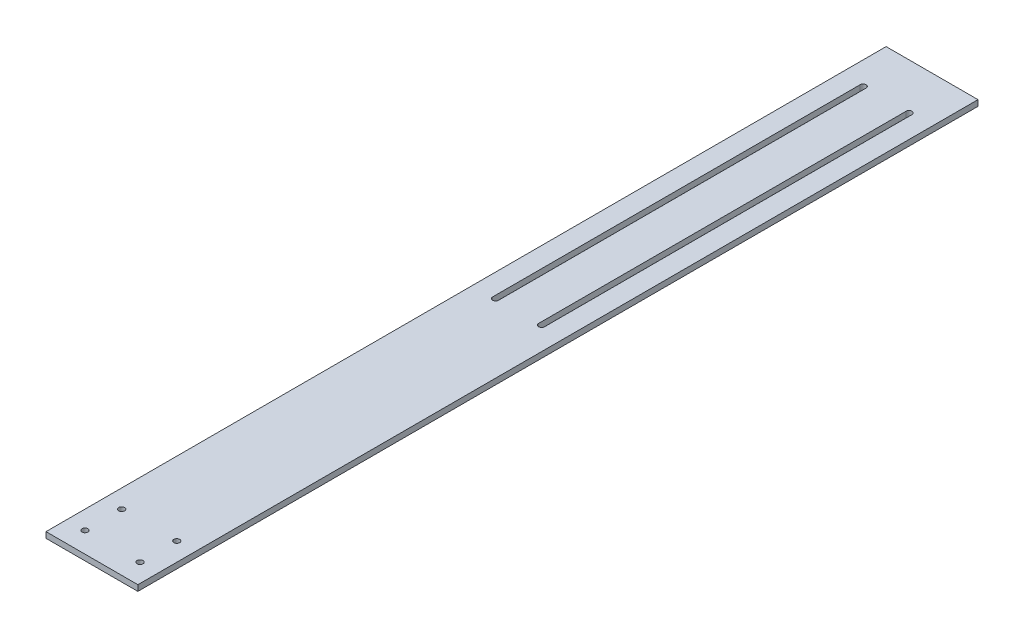
SolidWorks part; units mm, degrees
material "Acrylic (Medium-high impact)"
ref_plane "Front Plane" through (0, 0, 0) normal (0, 0, 1) x (1, 0, 0)
ref_plane "Top Plane" through (0, 0, 0) normal (0, 1, 0) x (1, 0, 0)
ref_plane "Right Plane" through (0, 0, 0) normal (1, 0, 0) x (0, 0, -1)
sketch "Sketch1" plane through (0, 0, 0) normal (0, 1, 0) x (1, 0, 0)
  line L1 (-25, 228.6) -> (25, 228.6)
  line L2 (-25, 228.6) -> (-25, -228.6)
  line L3 (-25, -228.6) -> (25, -228.6)
  line L4 (25, 228.6) -> (25, -228.6)
  line L5 (-25, 228.6) -> (25, -228.6) construction
  line L6 (-25, -228.6) -> (25, 228.6) construction
  point P0 (0, 0)
  dimension "D1" = 50
  dimension "D2" = 457.2
extrude "Boss-Extrude1" add sketch "Sketch1" along normal blind 3.175 contours L2 L3 L4 L1
sketch "Sketch2" plane through (0, 0, 0) normal (0, -1, 0) x (1, 0, 0)
  line L0 (-12.5, -3.6) -> (-12.5, -203.6) construction
  line L1 (-10.9, -3.6) -> (-10.9, -203.6)
  line L2 (-14.1, -3.6) -> (-14.1, -203.6)
  line L3 (0, 228.6) -> (0, -228.6) construction
  line L4 (-25, 228.6) -> (25, 228.6) construction
  line L5 (-25, -228.6) -> (25, -228.6) construction
  line L6 (0, -228.6) -> (-25, -228.6) construction
  line L7 (12.5, -3.6) -> (12.5, -203.6) construction
  line L8 (10.9, -3.6) -> (10.9, -203.6)
  line L9 (14.1, -3.6) -> (14.1, -203.6)
  arc A0 (-10.9, -3.6) -> (-14.1, -3.6) centre (-12.5, -3.6) ccw
  arc A1 (-14.1, -203.6) -> (-10.9, -203.6) centre (-12.5, -203.6) ccw
  arc A2 (10.9, -3.6) -> (14.1, -3.6) centre (12.5, -3.6) cw
  arc A3 (14.1, -203.6) -> (10.9, -203.6) centre (12.5, -203.6) cw
  point P2 (-12.5, -103.6)
  point P13 (-12.5, -228.6)
  point P18 (12.5, -103.6)
  dimension "D1" = 200
  dimension "D2" = 3.2
  dimension "D3" = 125
extrude "Cut-Extrude1" cut sketch "Sketch2" against normal through all
hole_wizard "M3 Clearance Hole1" positions "Sketch3" profile "Sketch4" hole size "M3" standard "ANSI Metric" end condition through all
sketch "Sketch3" plane through (0, 0, 0) normal (0, -1, 0) x (-1, 0, 0)
  line L1 (-15, -197.425) -> (15, -197.425)
  line L2 (-15, -197.425) -> (-15, -217.425)
  line L3 (-15, -217.425) -> (15, -217.425)
  line L4 (15, -197.425) -> (15, -217.425)
  line L5 (-15, -197.425) -> (15, -217.425) construction
  line L6 (-15, -217.425) -> (15, -197.425) construction
  line L7 (25, -228.6) -> (-25, -228.6) construction
  point P2 (15, -217.425)
  point P39 (-15, -197.425)
  point P40 (-15, -217.425)
  point P41 (15, -197.425)
  point P44 (0, -207.425)
  dimension "D1" = 30
  dimension "D2" = 20
  dimension "D3" = 21.175
sketch "Sketch4" plane through (-15, 0, 217.425) normal (1, 0, 0) x (0, 0, -1)
  line L0 (0, 0) -> (0, 3.175)
  line L1 (0, 3.175) -> (1.6, 3.175)
  line L2 (1.6, 3.175) -> (1.6, 0)
  line L5 (1.6, 0) -> (0, 0)
  line L11 (0, -6.35) -> (0, 107.95) construction
  dimension "Thru Hole Dia." = 3.2
  dimension "Thru Hole Depth" = 3.175
